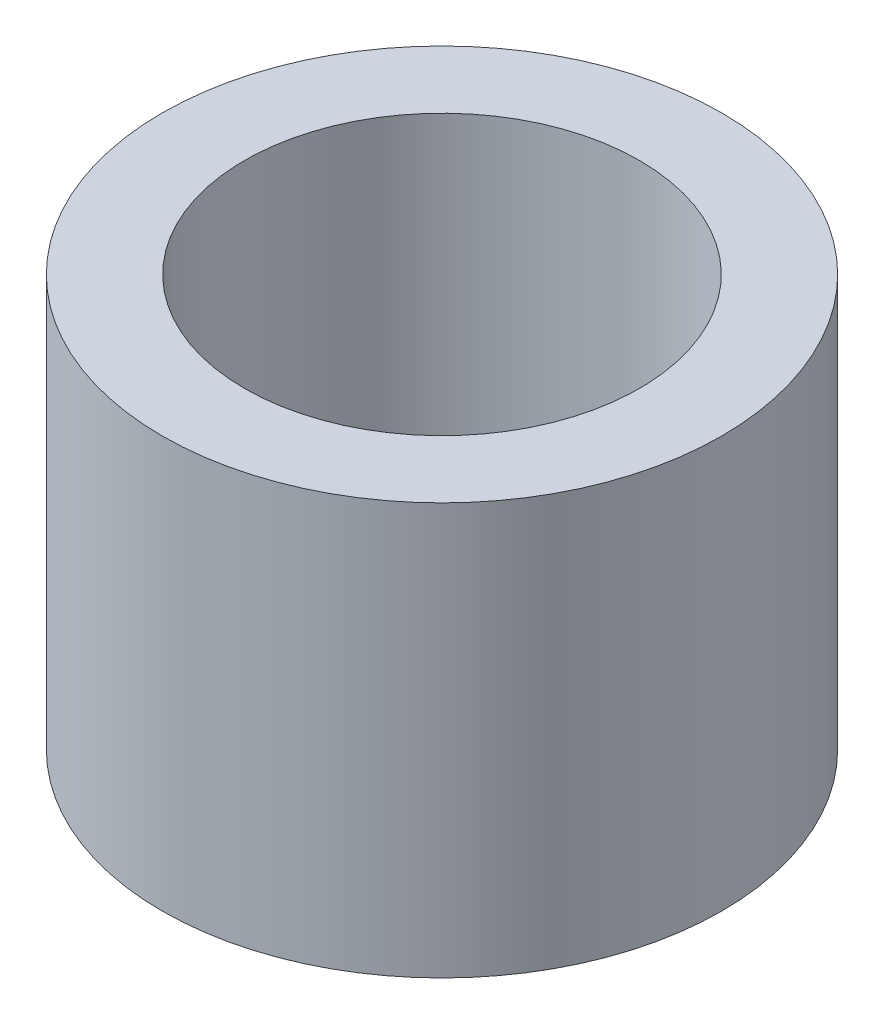
SolidWorks part; units mm, degrees
material "Phosphor bronze 10% D, UNS C52400"
ref_plane "Front Plane" through (0, 0, 0) normal (0, 0, 1) x (1, 0, 0)
ref_plane "Top Plane" through (0, 0, 0) normal (0, 1, 0) x (1, 0, 0)
ref_plane "Right Plane" through (0, 0, 0) normal (1, 0, 0) x (0, 0, -1)
sketch "Sketch1" plane through (0, 0, 0) normal (0, 1, 0) x (1, 0, 0)
  circle A0 centre (0, 0) radius 17
  circle A1 centre (0, 0) radius 12
  dimension "D1" = 34
  dimension "D2" = 24
extrude "Boss-Extrude1" add sketch "Sketch1" along normal mid plane 25
